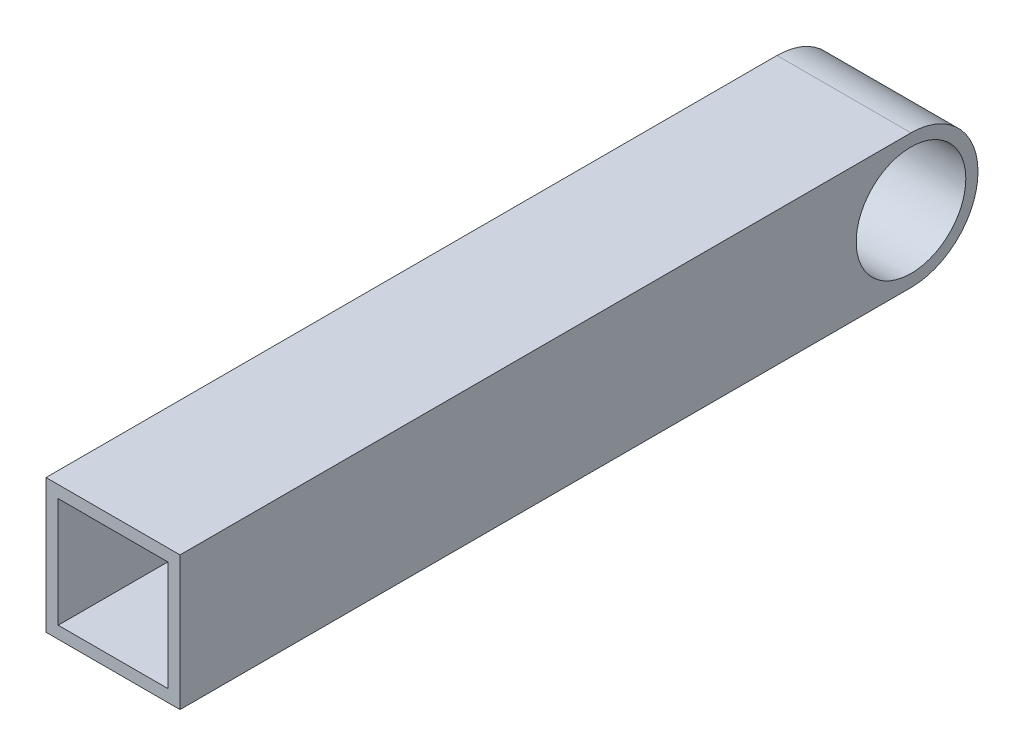
SolidWorks part; units mm, degrees
ref_plane "Front Plane" through (0, 0, 0) normal (0, 0, 1) x (1, 0, 0)
ref_plane "Top Plane" through (0, 0, 0) normal (0, 1, 0) x (1, 0, 0)
ref_plane "Right Plane" through (0, 0, 0) normal (1, 0, 0) x (0, 0, -1)
sketch "Sketch1" plane through (0, 0, 0) normal (0, 0, 1) x (1, 0, 0)
  line L5 (-27.5, -27.5) -> (27.5, -27.5)
  line L6 (-27.5, -27.5) -> (-27.5, 27.5)
  line L7 (-27.5, 27.5) -> (27.5, 27.5)
  line L8 (27.5, -27.5) -> (27.5, 27.5)
  line L9 (-27.5, -27.5) -> (27.5, 27.5) construction
  line L10 (-27.5, 27.5) -> (27.5, -27.5) construction
  point P0 (0, 0)
  dimension "D1" = 55
  dimension "D2" = 55
extrude "Boss-Extrude1" add sketch "Sketch1" along normal blind 327.5
sketch "Sketch2" plane through (27.5, 0, 0) normal (1, 0, 0) x (0, 0, -1)
  line L2 (0, -27.5) -> (0, 27.5) construction
  circle A0 centre (-27.5, 0) radius 27.5
  circle A1 centre (-27.5, 0) radius 22.5
  dimension "D1" = 45
  dimension "D2" = 55
extrude "Cut-Extrude1" cut sketch "Sketch2" against normal up to surface (55 mm away) contours A1 up to face at (-27.5, 0, 163.75)
sketch "Sketch3" plane through (27.5, 0, 0) normal (1, 0, 0) x (0, 0, -1)
  line L1 (-27.5, 27.5) -> (0, 27.5)
  line L2 (0, 27.5) -> (0, 0)
  line L3 (0, 0) -> (0, -27.5)
  line L4 (0, -27.5) -> (-27.5, -27.5)
  arc A2 (-27.5, -27.5) -> (-27.5, 27.5) centre (-27.5, 0) ccw
  line M2 (0, -27.5) -> (0, 27.5)
  line M3 (0, 27.5) -> (-327.5, 27.5)
  line M5 (-327.5, -27.5) -> (0, -27.5)
extrude "Cut-Extrude2" cut sketch "Sketch3" against normal up to surface (55 mm away) contours A2 M2 M3 | A2 M5 M2 up to face at (-27.5, 0, 5)
sketch "Sketch4" plane through (0, 0, 327.5) normal (0, 0, 1) x (1, 0, 0)
  line L1 (-22.5, -22.5) -> (22.5, -22.5)
  line L2 (-22.5, -22.5) -> (-22.5, 22.5)
  line L3 (-22.5, 22.5) -> (22.5, 22.5)
  line L4 (22.5, -22.5) -> (22.5, 22.5)
  line L5 (-22.5, -22.5) -> (22.5, 22.5) construction
  line L6 (-22.5, 22.5) -> (22.5, -22.5) construction
  point P0 (0, 0)
  dimension "D1" = 45
  dimension "D2" = 45
extrude "Cut-Extrude3" cut sketch "Sketch4" against normal blind 280
